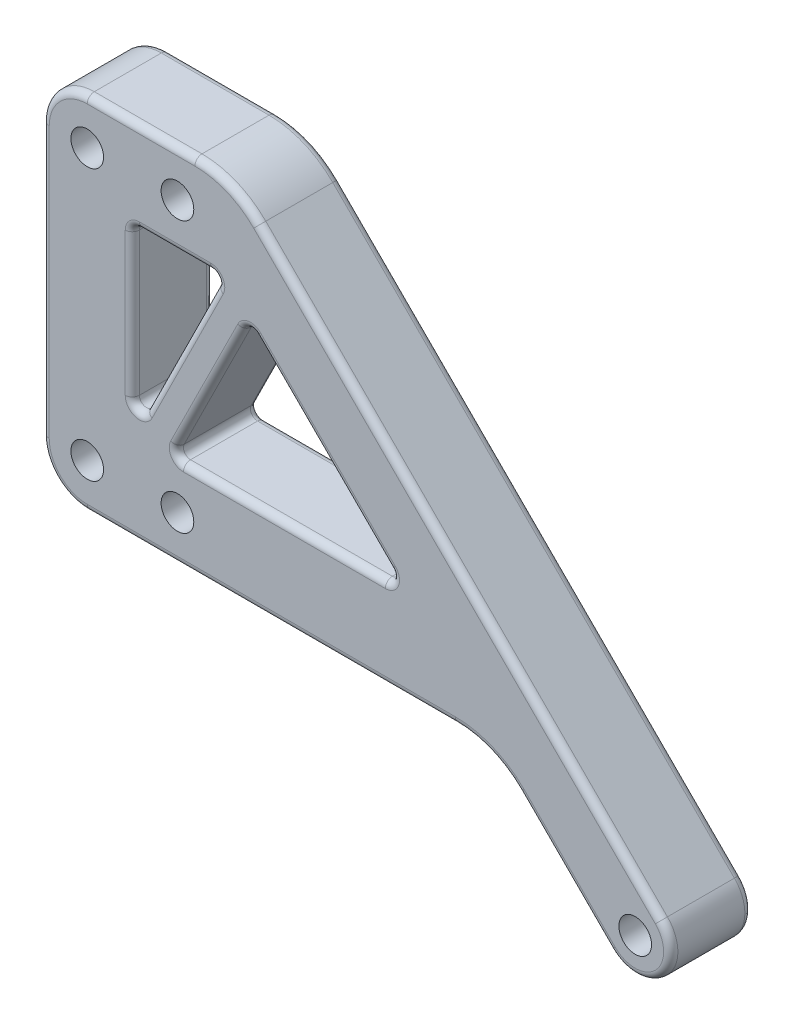
SolidWorks part; units mm, degrees
ref_plane "Front Plane" through (0, 0, 0) normal (0, 0, 1) x (1, 0, 0)
ref_plane "Top Plane" through (0, 0, 0) normal (0, 1, 0) x (1, 0, 0)
ref_plane "Right Plane" through (0, 0, 0) normal (1, 0, 0) x (0, 0, -1)
sketch "Sketch1" plane through (0, 0, 0) normal (0, 0, 1) x (1, 0, 0)
  line L0 (-83.5, 63.8) -> (-83.5, 13)
  line L1 (-83.5, 63.8) -> (-56.7289, 63.8)
  line L3 (-83.5, 13) -> (-70.8, 13)
  line L4 (-70.8, 13) -> (-20.0711, 13)
  line L5 (-20.0711, 13) -> (-3.5355, -3.5355)
  line L6 (3.5355, 3.5355) -> (-56.7289, 63.8)
  line L8 (-70.8, 25.7) -> (-32.7711, 25.7)
  line L10 (-32.7711, 25.7) -> (-58.1711, 51.1)
  line L11 (-58.1711, 51.1) -> (-70.8, 51.1)
  line L12 (-70.8, 51.1) -> (-70.8, 25.7)
  line L13 (-70.8, 25.7) -> (-58.1711, 51.1)
  line L14 (-65.2161, 25.7) -> (-54.4415, 47.3704)
  line L15 (3.5355, 59.9645) -> (-24.6789, 31.75)
  line L16 (-31.75, 38.8211) -> (-3.5355, 67.0355)
  circle A0 centre (0, 0) radius 50.8 construction
  circle A1 centre (0, 0) radius 70.8 construction
  circle A2 centre (0, 0) radius 2.3
  arc A3 (-3.5355, -3.5355) -> (3.5355, 3.5355) centre (0, 0) ccw
  circle A4 centre (-77.15, 19.35) radius 2.3
  circle A5 centre (-77.15, 57.45) radius 2.3
  circle A6 centre (-64.45, 19.35) radius 2.3
  circle A7 centre (-64.45, 57.45) radius 2.3
  circle A8 centre (0, 63.5) radius 50.8 construction
  circle A9 centre (0, 63.5) radius 2.3
  circle A10 centre (0, 63.5) radius 5
  point P6 (-70.8, 0)
  dimension "D1" = 101.6
  dimension "D2" = 141.6
  dimension "D6" = 4.6
  dimension "D7" = 10
  dimension "D12" = 6.35
  dimension "D17" = 4.6
  dimension "D21" = 101.6
  dimension "D23" = 4.6
  dimension "D24" = 10
  dimension "D3" = 12.7
  dimension "D4" = 50.8
  dimension "D5" = 13
  dimension "D8" = 135
  dimension "D9" = 12.7
  dimension "D10" = 12.7
  dimension "D11" = 12.7
  dimension "D13" = 6.35
  dimension "D14" = 6.35
  dimension "D15" = 6.35
  dimension "D16" = 12.7
  dimension "D18" = 5
  dimension "D19" = 12.7
  dimension "D20" = 38.1
  dimension "D22" = 63.5
extrude "Boss-Extrude1" add sketch "Sketch1" along normal blind 11.43 contours L5 A3 L6 L1 L0 L3 L4 A6 A5 A4 L12 L11 L10 L8 A2 | L8 L14 L10 L13
fillet "Fillet2" radius 1 6 edges at (-32.7711, 25.7, 5.715) (-65.2161, 25.7, 5.715) (-70.8, 25.7, 5.715) (-70.8, 51.1, 5.715) (-58.1711, 51.1, 5.715) (-54.4415, 47.3704, 5.715)
fillet "Fillet3" radius 6.35 2 edges at (-83.5, 13, 5.715) (-83.5, 63.8, 5.715)
fillet "Fillet4" radius 12.7 2 edges at (-20.0711, 13, 5.715) (-56.7289, 63.8, 5.715)
fillet "Fillet5" radius 1 44 edges at (-24.7368, 31.8079, 0) (3.5355, -3.5355, 0) (-9.9434, 2.8724, 0) (-20.4715, 12.0333, 0) (-51.2408, 13, 0) (-81.6401, 14.8599, 0) (-83.5, 38.4, 0) (-81.6401, 61.9401, 0) (-69.5697, 63.8, 0) (-57.1294, 62.8333, 0) (-24.7368, 31.8079, 11.43) (3.5355, -3.5355, 11.43) (-9.9434, 2.8724, 11.43) (-20.4715, 12.0333, 11.43) (-51.2408, 13, 11.43) (-81.6401, 14.8599, 11.43) (-83.5, 38.4, 11.43) (-81.6401, 61.9401, 11.43) (-69.5697, 63.8, 11.43) (-57.1294, 62.8333, 11.43) (-70.0287, 28.9839, 0) (-70.8, 40.0287, 0) (-70.5071, 50.8071, 0) (-64.7925, 51.1, 0) (-58.935, 50.6267, 0) (-64.4521, 26.1733, 0) (-49.3937, 25.7, 0) (-34.2614, 26.3173, 0) (-43.9681, 36.8971, 0) (-54.3265, 46.6668, 0) (-64.4521, 26.1733, 11.43) (-49.3937, 25.7, 11.43) (-34.2614, 26.3173, 11.43) (-43.9681, 36.8971, 11.43) (-54.3265, 46.6668, 11.43) (-70.5071, 50.8071, 11.43) (-64.7925, 51.1, 11.43) (-58.935, 50.6267, 11.43) (-63.8971, 39.5835, 11.43) (-70.0287, 28.9839, 11.43) (-63.8971, 39.5835, 0) (-59.7791, 36.6352, 0) (-59.7791, 36.6352, 11.43) (-70.8, 40.0287, 11.43)
